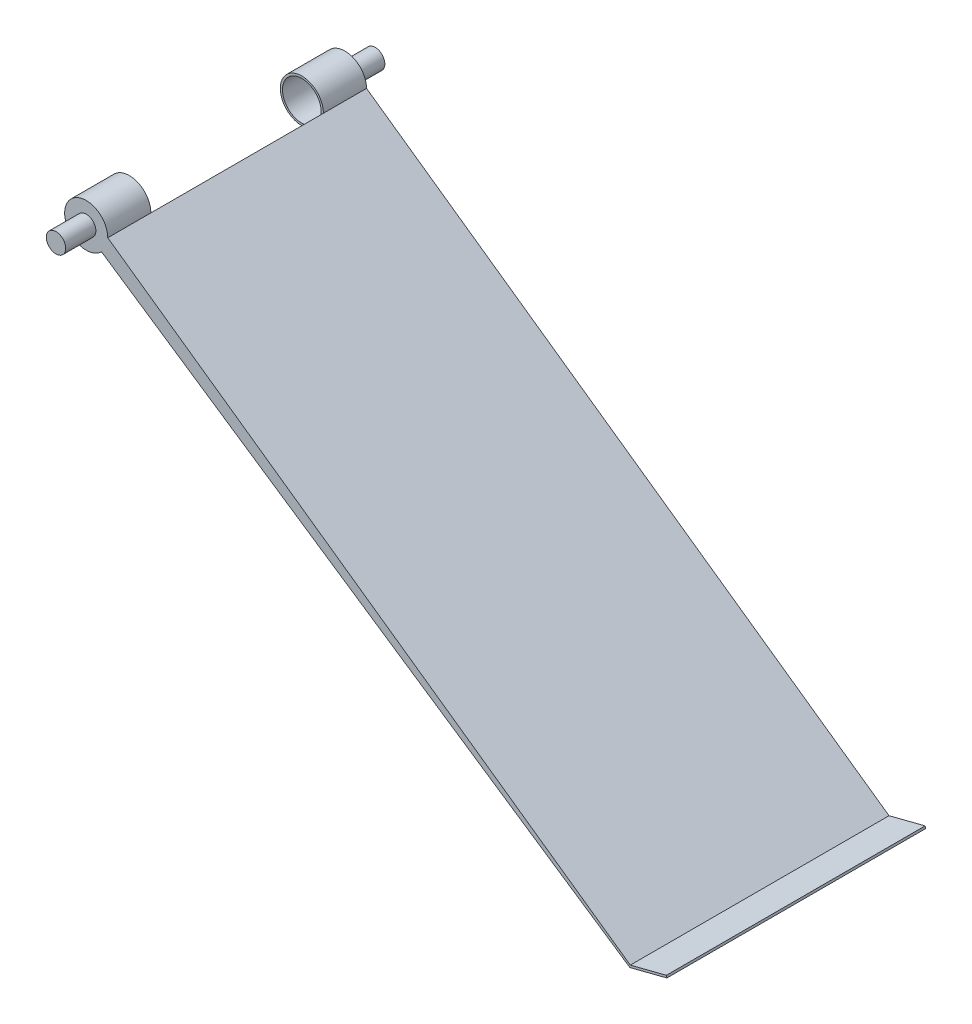
SolidWorks part; units mm, degrees
ref_plane "Front Plane" through (0, 0, 0) normal (0, 0, 1) x (1, 0, 0)
ref_plane "Top Plane" through (0, 0, 0) normal (0, 1, 0) x (1, 0, 0)
ref_plane "Right Plane" through (0, 0, 0) normal (1, 0, 0) x (0, 0, -1)
sketch "Sketch1" plane through (0, 0, 0) normal (0, 0, 1) x (1, 0, 0)
  circle A1 centre (0, 0) radius 0.5
  dimension "D2" = 1
extrude "Boss-Extrude1" add sketch "Sketch1" against normal blind 1
sketch "Sketch2" plane through (0, 0, -1) normal (0, 0, -1) x (-1, 0, 0)
  circle A0 centre (0, 0) radius 0.45
  dimension "D1" = 0.9
extrude "Cut-Extrude1" cut sketch "Sketch2" against normal blind 0.9
sketch "Sketch3" plane through (0, 0, 0) normal (0, 0, 1) x (1, 0, 0)
  circle A0 centre (0, 0) radius 0.225
  dimension "D1" = 0.45
extrude "Boss-Extrude2" add sketch "Sketch3" along normal blind 0.7
sketch "Sketch4" plane through (0, 0, 0) normal (0, 0, 1) x (1, 0, 0)
  line L2 (12.6155, -8.5468) -> (0.5, 0)
  line L6 (12.6061, -8.6008) -> (0.3536, -0.3536)
  line L8 (12.6061, -8.6008) -> (13.4648, -8.3811)
  line L9 (13.4648, -8.3811) -> (13.4524, -8.3326)
  line L10 (13.4524, -8.3326) -> (12.6155, -8.5468)
  circle A0 centre (0, 0) radius 0.5 construction
  arc A1 (0.3536, -0.3536) -> (0.5, 0) centre (0, 0) ccw
  dimension "D1" = 0.05
  dimension "D2" = 0.8863
  dimension "D3" = 0.05
extrude "Boss-Extrude3" add sketch "Sketch4" against normal blind 6
ref_plane "Plane1" through (0, 0, 3) normal (0, 0, 1) x (1, 0, 0)
ref_plane "Plane2" through (0, 0, -3) normal (0, 0, 1) x (1, 0, 0)
mirror "Mirror1" about plane through (0, 0, -3) normal (0, 0, 1) of "Cut-Extrude1", "Boss-Extrude2", "Boss-Extrude1"
